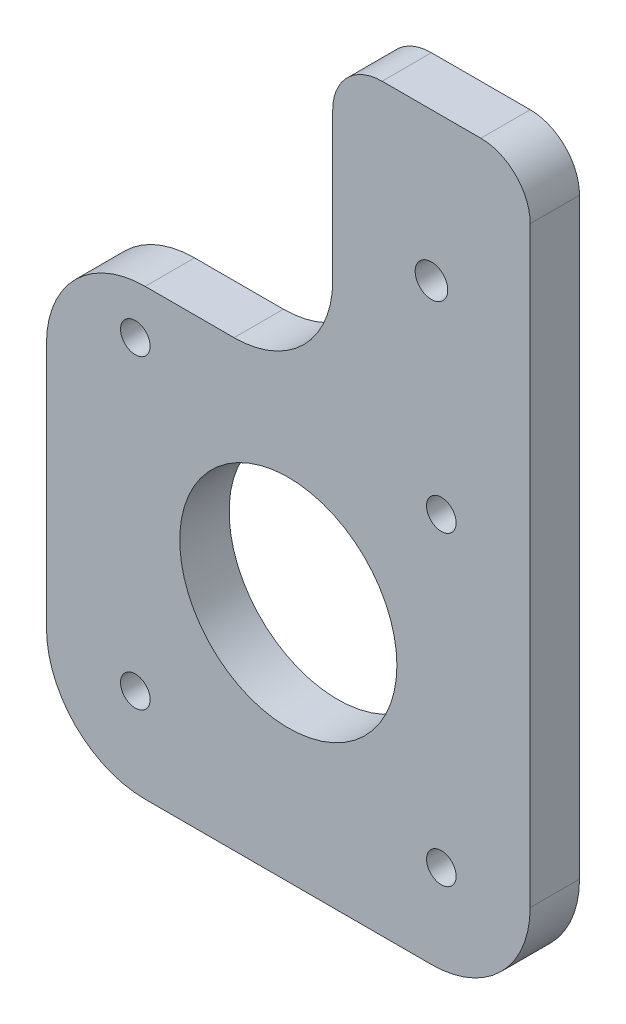
SolidWorks part; units mm, degrees
ref_plane "Front Plane" through (0, 0, 0) normal (0, 0, 1) x (1, 0, 0)
ref_plane "Top Plane" through (0, 0, 0) normal (0, 1, 0) x (1, 0, 0)
ref_plane "Right Plane" through (0, 0, 0) normal (1, 0, 0) x (0, 0, -1)
sketch "Sketch1" plane through (0, 0, 0) normal (0, 0, 1) x (1, 0, 0)
  line L0 (23.8834, 91.6472) -> (23.8834, -9.2883) construction
  line L5 (43.8834, 91.6472) -> (43.8834, -9.2883) construction
  line L6 (23.8834, 30) -> (43.8834, 30)
  line L7 (-20.1977, 30) -> (97.1776, 30) construction
  line L8 (0, 0) -> (-5.1166, 0)
  line L9 (-5.1166, 0) -> (-5.1166, -45)
  line L13 (-27.2281, -5) -> (34.1242, -5) construction
  line L14 (-27.2281, -36) -> (34.1242, -36) construction
  line L15 (3.8834, -5) -> (3.8834, -36) construction
  line L16 (34.8834, -5) -> (34.8834, -36) construction
  line L17 (3.8834, -5) -> (34.8834, -36) construction
  line L18 (34.8834, -5) -> (3.8834, -36) construction
  line L19 (23.8834, 30) -> (23.8834, 0)
  line L20 (23.8834, 0) -> (0, 0)
  line L21 (43.8834, 30) -> (43.8834, -45)
  line L22 (43.8834, -45) -> (-5.1166, -45)
  line L23 (33.8834, 38.3571) -> (33.8834, -17.7124) construction
  circle A5 centre (3.8834, -5) radius 1.5
  circle A6 centre (34.8834, -5) radius 1.5
  circle A7 centre (24.8397, 9.6295) radius 12 construction
  circle A8 centre (3.8834, -36) radius 1.5
  circle A9 centre (34.8834, -36) radius 1.5
  circle A10 centre (19.3834, -20.5) radius 11
  circle A13 centre (33.8834, 15) radius 1.65
  point P1 (19.3834, -45)
  point P3 (11.9417, 0)
  point P14 (33.8834, 30)
  dimension "D5" = 5
  dimension "D6" = 30
  dimension "D11" = 31
  dimension "D7" = 15
  dimension "D2" = 9
  dimension "D3" = 20
  dimension "D4" = 9
  dimension "D12" = 31
  dimension "D14" = 9
extrude "Boss-Extrude1" add sketch "Sketch1" along normal blind 5
fillet "Fillet1" radius 10 4 edges at (-5.1166, 0, 2.5) (23.8834, 0, 2.5) (-5.1166, -45, 2.5) (43.8834, -45, 2.5)
fillet "Fillet2" radius 5 2 edges at (23.8834, 30, 2.5) (43.8834, 30, 2.5)
